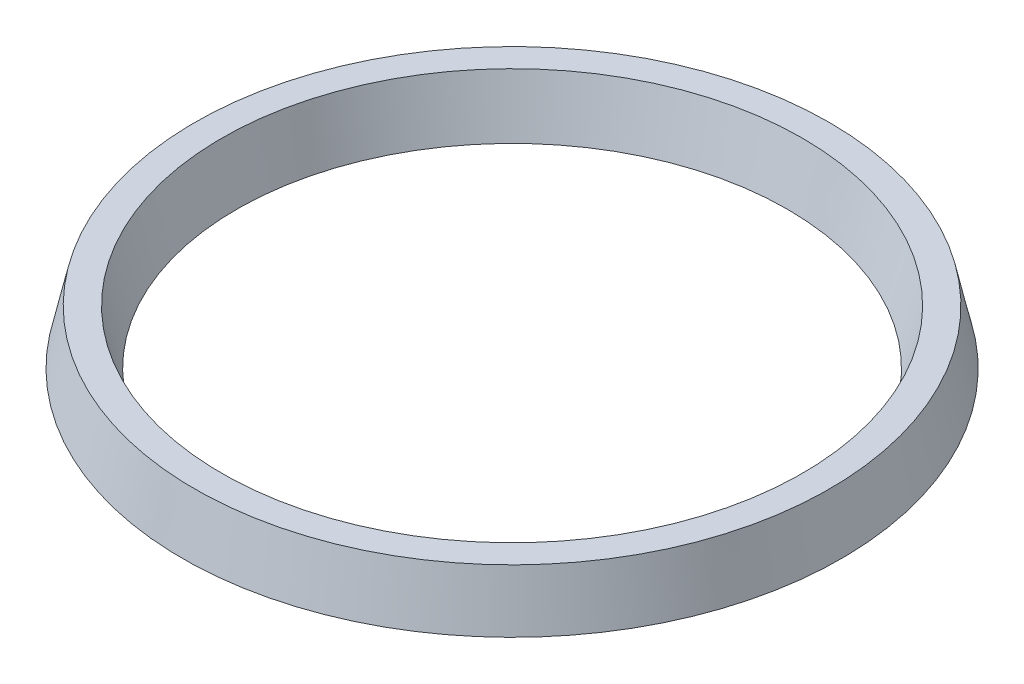
SolidWorks part; units mm, degrees
ref_plane "Front Plane" through (0, 0, 0) normal (0, 0, 1) x (1, 0, 0)
ref_plane "Top Plane" through (0, 0, 0) normal (0, 1, 0) x (1, 0, 0)
ref_plane "Right Plane" through (0, 0, 0) normal (1, 0, 0) x (0, 0, -1)
sketch "Sketch1" plane through (0, 0, 0) normal (0, 0, 1) x (1, 0, 0)
  line L0 (0, 0) -> (0, 11.625) construction
  line L1 (0, 0) -> (-67.31, 0) construction
  line L2 (3, 6) -> (-3, 6)
  line L3 (-3, 6) -> (-6.3049, -6)
  line L4 (-6.3049, -6) -> (-3.3049, -6)
  line L5 (-3.3049, -6) -> (-2.0378, -1.399)
  line L6 (1.6817, -1.4879) -> (2.6951, -6)
  line L7 (2.6951, -6) -> (5.6951, -6)
  line L8 (5.6951, -6) -> (3, 6)
  line L9 (-67.31, 0) -> (-67.31, 11.625) construction
  arc A1 (-2.0378, -1.399) -> (1.6817, -1.4879) centre (-0.1891, -1.9081) cw
  dimension "D1" = 6
  dimension "D2" = 12
  dimension "D3" = 3
  dimension "D4" = 12
  dimension "D5" = 12
  dimension "D6" = 6
  dimension "D7" = 3
  dimension "D8" = 67.31
revolve "Revolve1" add sketch "Sketch1" angle 360 about L9
